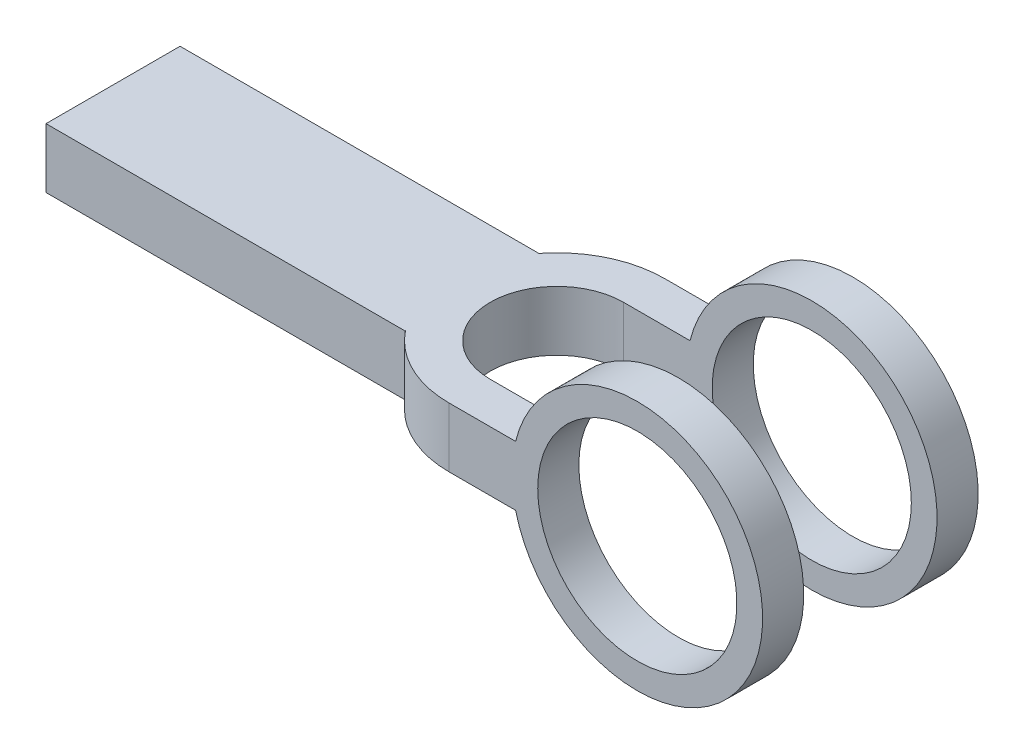
SolidWorks part; units mm, degrees
other "Markup1"
sketch "Sketch5" plane through (-156.0544, -33.5927, -37.924) normal (-0.13, -0.4618, -0.8774) x (-0.8548, 0.5006, -0.1368)
ref_plane "Front Plane" through (0, 0, 0) normal (0, 0, 1) x (1, 0, 0)
ref_plane "Top Plane" through (0, 0, 0) normal (0, 1, 0) x (1, 0, 0)
ref_plane "Right Plane" through (0, 0, 0) normal (1, 0, 0) x (0, 0, -1)
sketch "Sketch1" plane through (0, 0, 0) normal (0, 1, 0) x (1, 0, 0)
  line L0 (0, 37.924) -> (23.7123, 37.924)
  line L1 (-29.7983, 23.4583) -> (-156.0544, 23.4583)
  line L2 (-29.7983, -23.4583) -> (-29.7983, -23.7123)
  line L3 (-29.7983, -23.7123) -> (-156.0544, -23.7123)
  line L4 (-156.0544, 23.4583) -> (-156.0544, -23.7123)
  line L5 (23.7123, 37.924) -> (23.7123, 23.4583)
  line L6 (23.7123, -37.924) -> (0, -37.924)
  line L7 (23.7123, 23.4583) -> (0, 23.4583)
  line L8 (0, -23.4583) -> (23.7123, -23.4583)
  line L9 (23.7123, -23.4583) -> (23.7123, -37.924)
  arc A0 (0, 37.924) -> (-29.7983, 23.4583) centre (0, 0) ccw
  arc A1 (0, 23.4583) -> (0, -23.4583) centre (0, 0) ccw
  arc A2 (-29.7983, -23.4583) -> (0, -37.924) centre (0, 0) ccw
extrude "Boss-Extrude1" add sketch "Sketch1" along normal blind 21
sketch "Sketch2" plane through (0, 0, -23.4583) normal (0, 0, 1) x (1, 0, 0)
  circle A0 centre (66.2253, 10.5) radius 44.0927
  circle A1 centre (66.2253, 10.5) radius 35.0395
extrude "Boss-Extrude2" add sketch "Sketch2" against normal up to surface (14.4657 mm away) up to face at (11.8562, 10.5, -37.924)
sketch "Sketch4" plane through (0, 0, 23.4583) normal (0, 0, -1) x (-1, 0, 0)
  circle A0 centre (-66.2253, 10.5) radius 44.0927
  circle A1 centre (-66.2253, 10.5) radius 35.0395
extrude "Boss-Extrude3" add sketch "Sketch4" against normal up to surface (14.4657 mm away) up to face at (11.8562, 10.5, 37.924)
